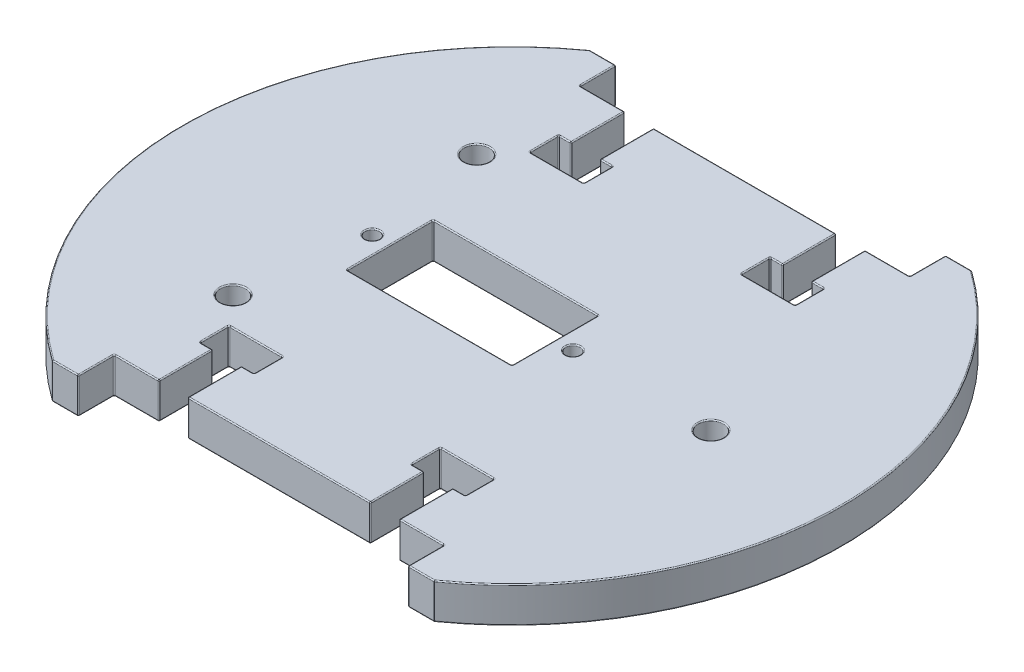
SolidWorks part; units mm, degrees
ref_plane "Front Plane" through (0, 0, 0) normal (0, 0, 1) x (1, 0, 0)
ref_plane "Top Plane" through (0, 0, 0) normal (0, 1, 0) x (1, 0, 0)
ref_plane "Right Plane" through (0, 0, 0) normal (1, 0, 0) x (0, 0, -1)
sketch "Sketch1" plane through (0, 0, 0) normal (0, 1, 0) x (1, 0, 0)
  line L0 (-26.6411, 37.5) -> (-23, 37.5)
  line L1 (23, 37.5) -> (26.6411, 37.5)
  line L3 (-23, 37.5) -> (-23, 32.5)
  line L4 (-23, 32.5) -> (23, 32.5)
  line L5 (23, 37.5) -> (23, 32.5)
  line L6 (0, 0) -> (-46, 0) construction
  line L7 (-26.6411, -37.5) -> (-23, -37.5)
  line L8 (23, -37.5) -> (26.6411, -37.5)
  line L9 (23, -37.5) -> (23, -32.5)
  line L10 (-23, -32.5) -> (23, -32.5)
  line L11 (-23, -37.5) -> (-23, -32.5)
  line L12 (27.75, 0) -> (-21.93, 0) construction
  line L13 (-17, -6) -> (6, -6)
  line L14 (-17, -6) -> (-17, 6)
  line L15 (-17, 6) -> (6, 6)
  line L16 (6, -6) -> (6, 6)
  line L17 (-17, -6) -> (6, 6) construction
  line L18 (-17, 6) -> (6, -6) construction
  line L19 (-21.93, 17) -> (-21.93, -17) construction
  arc A0 (-26.6411, 37.5) -> (-26.6411, -37.5) centre (0, 0) ccw
  arc A1 (26.6411, -37.5) -> (26.6411, 37.5) centre (0, 0) ccw
  circle A2 centre (-19.5, 0) radius 1
  circle A3 centre (8.5, 0) radius 1
  circle A4 centre (-21.93, 17) radius 1.75
  circle A5 centre (-21.93, -17) radius 1.75
  circle A6 centre (27.75, 0) radius 1.75
  point P9 (0, 32.5)
  point P16 (-5.5, 0)
  dimension "D1" = 92
  dimension "D8" = 2
  dimension "D10" = 2
  dimension "D16" = 3.5
  dimension "D2" = 37.5
  dimension "D3" = 46
  dimension "D4" = 5
  dimension "D5" = 23
  dimension "D6" = 12
  dimension "D7" = 6
  dimension "D9" = 2.5
  dimension "D11" = 2.5
  dimension "D12" = 8.5
  dimension "D13" = 34
  dimension "D14" = 27.75
  dimension "D15" = 49.68
extrude "Boss-Extrude1" add sketch "Sketch1" along normal blind 5
sketch "Sketch5" plane through (0, 5, 0) normal (0, 1, 0) x (1, 0, 0)
  line L0 (23, 32.5) -> (-23, 32.5) construction
  line L1 (-16.75, 25) -> (-12.75, 25)
  line L2 (-16.75, 25) -> (-16.75, 32.5)
  line L3 (-16.75, 32.5) -> (-12.75, 32.5)
  line L4 (-12.75, 25) -> (-12.75, 32.5)
  line L5 (-16.75, 25) -> (-12.75, 32.5) construction
  line L6 (-16.75, 32.5) -> (-12.75, 25) construction
  line L7 (-23, 32.5) -> (-23, 37.5) construction
  line L8 (-18.5, 21) -> (-11, 21)
  line L9 (-18.5, 21) -> (-18.5, 25)
  line L10 (-18.5, 25) -> (-11, 25)
  line L11 (-11, 21) -> (-11, 25)
  line L12 (-18.5, 21) -> (-11, 25) construction
  line L13 (-18.5, 25) -> (-11, 21) construction
  line L14 (0, 0) -> (-17, 0) construction
  line L15 (-17, 6) -> (-17, -6) construction
  line L16 (0, 0) -> (0, 32.5) construction
  line L17 (18.5, 25) -> (11, 21) construction
  line L18 (18.5, 21) -> (11, 25) construction
  line L19 (16.75, 32.5) -> (12.75, 25) construction
  line L20 (16.75, 25) -> (12.75, 32.5) construction
  line L21 (11, 21) -> (11, 25)
  line L22 (18.5, 25) -> (11, 25)
  line L23 (18.5, 21) -> (18.5, 25)
  line L24 (18.5, 21) -> (11, 21)
  line L25 (12.75, 25) -> (12.75, 32.5)
  line L26 (16.75, 32.5) -> (12.75, 32.5)
  line L27 (16.75, 25) -> (16.75, 32.5)
  line L28 (16.75, 25) -> (12.75, 25)
  line L29 (16.75, -25) -> (12.75, -32.5) construction
  line L30 (16.75, -32.5) -> (12.75, -25) construction
  line L31 (18.5, -21) -> (11, -25) construction
  line L32 (18.5, -25) -> (11, -21) construction
  line L33 (-18.5, -25) -> (-11, -21) construction
  line L34 (-18.5, -21) -> (-11, -25) construction
  line L35 (-16.75, -32.5) -> (-12.75, -25) construction
  line L36 (-16.75, -25) -> (-12.75, -32.5) construction
  line L37 (16.75, -25) -> (12.75, -25)
  line L38 (16.75, -25) -> (16.75, -32.5)
  line L39 (16.75, -32.5) -> (12.75, -32.5)
  line L40 (12.75, -25) -> (12.75, -32.5)
  line L41 (18.5, -21) -> (11, -21)
  line L42 (18.5, -21) -> (18.5, -25)
  line L43 (18.5, -25) -> (11, -25)
  line L44 (11, -21) -> (11, -25)
  line L45 (-11, -21) -> (-11, -25)
  line L46 (-18.5, -25) -> (-11, -25)
  line L47 (-18.5, -21) -> (-18.5, -25)
  line L48 (-18.5, -21) -> (-11, -21)
  line L49 (-12.75, -25) -> (-12.75, -32.5)
  line L50 (-16.75, -32.5) -> (-12.75, -32.5)
  line L51 (-16.75, -25) -> (-16.75, -32.5)
  line L52 (-16.75, -25) -> (-12.75, -25)
  point P0 (-14.75, 28.75)
  point P7 (-14.75, 23)
  point P28 (14.75, 23)
  point P29 (14.75, 28.75)
  point P46 (14.75, -28.75)
  point P47 (14.75, -23)
  point P48 (-14.75, -23)
  point P49 (-14.75, -28.75)
  dimension "D1" = 6.25
  dimension "D2" = 4
  dimension "D3" = 7.5
  dimension "D4" = 4
  dimension "D5" = 7.5
extrude "Cut-Extrude1" cut sketch "Sketch5" against normal through all contours L45 L46 L47 L48 | L49 L50 L51 L52 | L42 L43 L44 L41 | L38 L39 L40 L37 | L27 L26 L25 L28 | L24 L21 L22 L23 | L4 L3 L2 L1 | L8 L11 L10 L9
fillet "Fillet1" radius 0.15 123 edges at (-16.75, 2.5, 25) (-11, 2.5, 21) (-11, 2.5, 25) (-18.5, 2.5, 25) (-18.5, 0, 23) (-17.625, 0, 25) (-11.875, 0, 25) (-11, 0, 23) (-14.75, 0, 21) (-17.625, 5, 25) (-11.875, 5, 25) (-11, 5, 23) (-14.75, 5, 21) (-12.75, 2.5, 32.5) (-16.75, 2.5, 32.5) (-12.75, 0, 28.75) (-16.75, 5, 28.75) (16.75, 2.5, -25) (16.75, 5, -28.75) (12.75, 5, -28.75) (18.5, 2.5, -21) (11, 2.5, -21) (11, 2.5, -25) (18.5, 2.5, -25) (14.75, 0, -21) (11, 0, -23) (17.625, 0, -25) (11.875, 0, -25) (18.5, 0, -23) (14.75, 5, -21) (11, 5, -23) (17.625, 5, -25) (18.5, 5, -23) (-16.75, 2.5, -25) (-12.75, 2.5, -32.5) (-12.75, 2.5, -25) (-16.75, 0, -28.75) (-12.75, 0, -28.75) (-12.75, 5, -28.75) (-18.5, 2.5, -25) (-11, 2.5, -25) (-11, 2.5, -21) (-14.75, 0, -21) (-11, 0, -23) (-17.625, 0, -25) (-11.875, 0, -25) (-18.5, 0, -23) (-14.75, 5, -21) (-11.875, 5, -25) (-18.5, 5, -23) (16.75, 5, 28.75) (12.75, 0, 28.75) (16.75, 0, 28.75) (16.75, 2.5, 32.5) (14.75, 5, 21) (11, 5, 23) (17.625, 5, 25) (18.5, 5, 23) (14.75, 0, 21) (11, 2.5, 21) (11, 2.5, 25) (18.5, 2.5, 25) (18.5, 2.5, 21) (12.75, 2.5, 25) (16.75, 2.5, 25) (27.75, 0, 1.75) (27.75, 5, 1.75) (-21.93, 0, 18.75) (-21.93, 5, 18.75) (-21.93, 0, -15.25) (-21.93, 5, -15.25) (8.5, 0, 1) (-19.5, 0, 1) (-19.5, 5, 1) (6, 0, 0) (-5.5, 0, -6) (-17, 0, 0) (6, 5, 0) (-5.5, 5, -6) (-17, 5, 0) (-5.5, 5, 6) (6, 2.5, 6) (-17, 2.5, 6) (-17, 2.5, -6) (6, 2.5, -6) (-46, 0, 0) (-24.8206, 0, 37.5) (-23, 0, 35) (19.875, 0, 32.5) (0, 0, 32.5) (-19.875, 0, 32.5) (24.8206, 0, 37.5) (46, 0, 0) (24.8206, 0, -37.5) (23, 0, -35) (-19.875, 0, -32.5) (0, 0, -32.5) (19.875, 0, -32.5) (-23, 0, -35) (-24.8206, 0, -37.5) (-46, 5, 0) (-24.8206, 5, 37.5) (-23, 5, 35) (19.875, 5, 32.5) (-19.875, 5, 32.5) (23, 5, 35) (24.8206, 5, 37.5) (46, 5, 0) (24.8206, 5, -37.5) (23, 5, -35) (-19.875, 5, -32.5) (0, 5, -32.5) (-24.8206, 5, -37.5) (-23, 2.5, -37.5) (-23, 2.5, -32.5) (23, 2.5, -32.5) (23, 2.5, -37.5) (26.6411, 2.5, -37.5) (26.6411, 2.5, 37.5) (23, 2.5, 37.5) (23, 2.5, 32.5) (-26.6411, 2.5, 37.5) (12.75, 2.5, 32.5)
